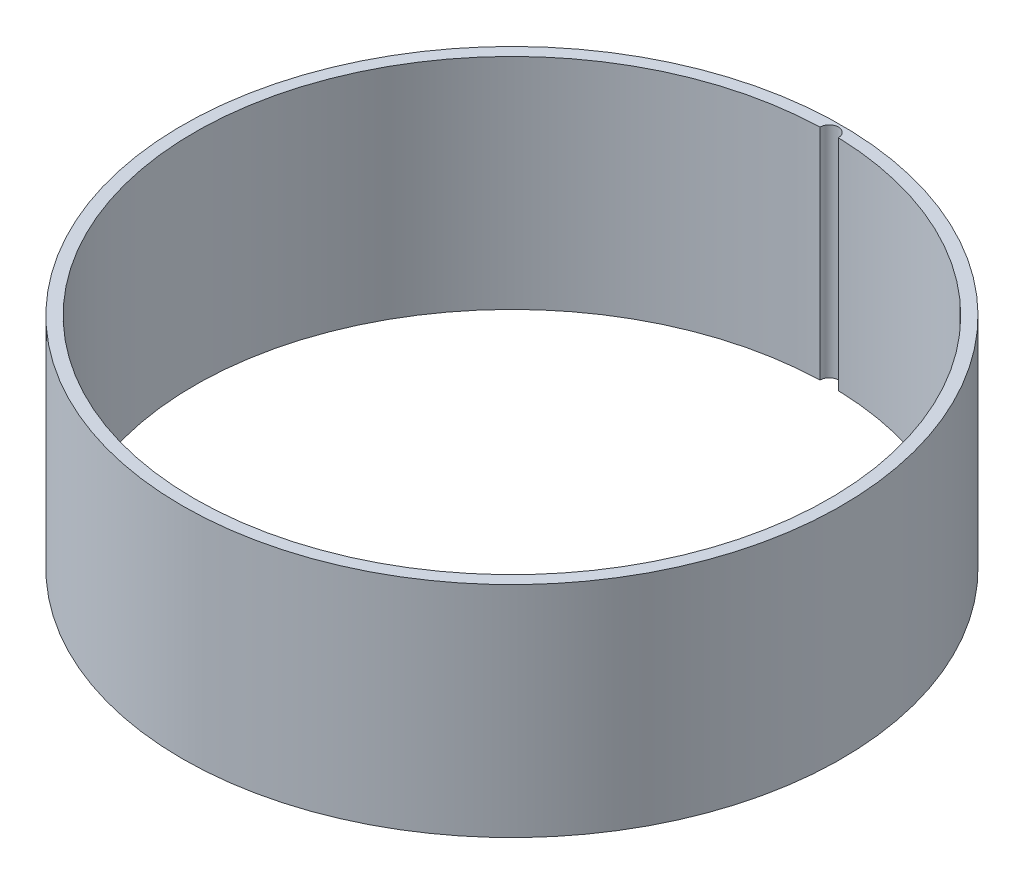
SolidWorks part; units mm, degrees
material "1.0038 (S235JRG2)"
ref_plane "Horní rovina" through (0, 0, 0) normal (0, 0, 1) x (1, 0, 0)
ref_plane "Přední rovina" through (0, 0, 0) normal (0, 1, 0) x (1, 0, 0)
ref_plane "Pravá rovina" through (0, 0, 0) normal (1, 0, 0) x (0, 0, -1)
sketch "Skica1" plane through (0, 0, 0) normal (0, 1, 0) x (1, 0, 0)
  line L0 (0, 30.9919) -> (0, 0) construction
  arc A0 (-0.7499, 25.9892) -> (0.7499, 25.9892) centre (0, 0) ccw
  circle A1 centre (0, 0) radius 27
  arc A2 (0.7499, 25.9892) -> (-0.7499, 25.9892) centre (0, 26) ccw
  dimension "D1" = 52
  dimension "D2" = 54
  dimension "D3" = 1.5
extrude "Přidat vysunutím1" add sketch "Skica1" along normal blind 17.95
